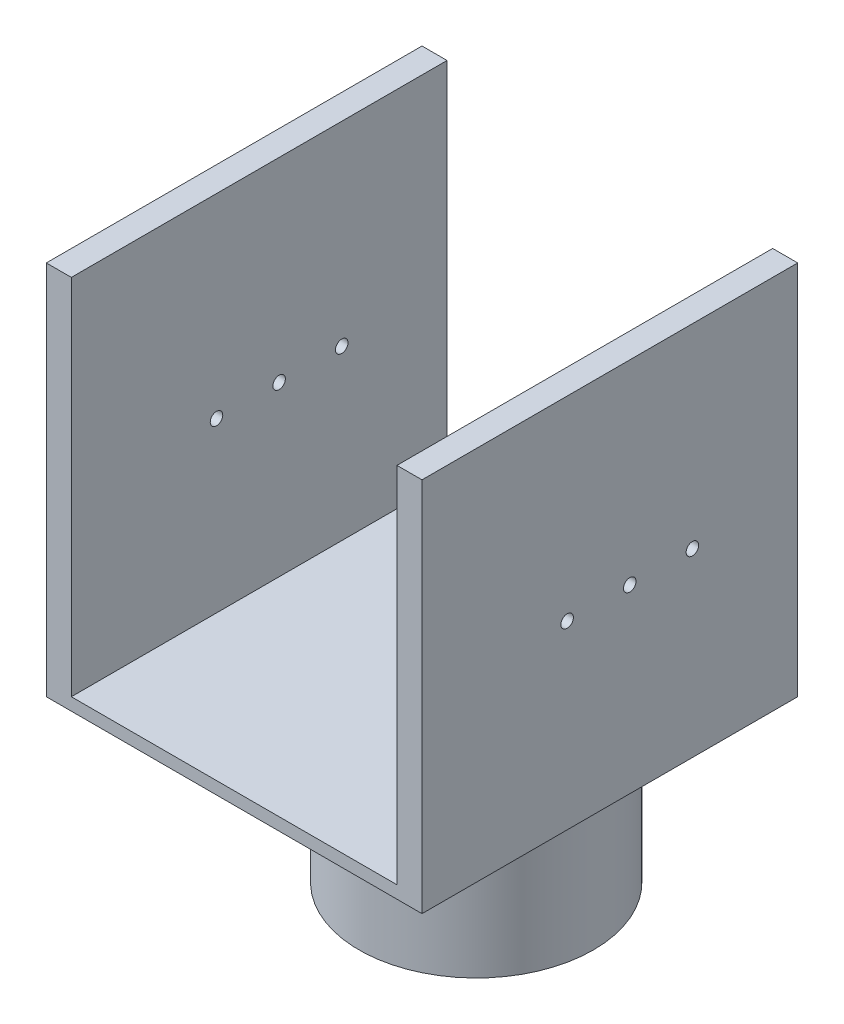
SolidWorks part; units mm, degrees
ref_plane "Front Plane" through (0, 0, 0) normal (0, 0, 1) x (1, 0, 0)
ref_plane "Top Plane" through (0, 0, 0) normal (0, 1, 0) x (1, 0, 0)
ref_plane "Right Plane" through (0, 0, 0) normal (1, 0, 0) x (0, 0, -1)
sketch "Sketch1" plane through (0, 0, 0) normal (0, 0, 1) x (1, 0, 0)
  line L0 (0, 0) -> (0, 30)
  line L1 (0, 30) -> (30, 30)
  line L2 (30, 30) -> (30, 0)
  line L3 (30, 0) -> (0, 0)
  line L4 (2, 30) -> (2, 1)
  line L5 (2, 1) -> (28, 1)
  line L6 (28, 1) -> (28, 30)
  dimension "D1" = 30
  dimension "D2" = 30
  dimension "D3" = 2
  dimension "D4" = 1
  dimension "D5" = 2
extrude "Boss-Extrude2" add sketch "Sketch1" along normal blind 30 contours L6 L5 L4 L1 L0 L3 L2
sketch "Sketch2" plane through (0, 0, 0) normal (0, -1, 0) x (1, 0, 0)
  circle A0 centre (15, 10.6696) radius 9.357
  dimension "D1" = 15
extrude "Boss-Extrude3" add sketch "Sketch2" along normal blind 15
sketch "Sketch3" plane through (0, -15, 0) normal (0, -1, 0) x (1, 0, 0)
  circle A0 centre (15, 10.6696) radius 8.5049
extrude "Cut-Extrude1" cut sketch "Sketch3" against normal blind 5.87
sketch "Sketch4" plane through (0, 0, 0) normal (-1, 0, 0) x (0, 0, 1)
  line L0 (8.4093, 14.4422) -> (18.4093, 14.4422)
  circle A0 centre (8.4093, 14.4422) radius 0.5
  circle A1 centre (13.4093, 14.4422) radius 0.5
  circle A2 centre (18.4093, 14.4422) radius 0.5
  dimension "D1" = 10
extrude "Cut-Extrude2" cut sketch "Sketch4" against normal blind 37.592
